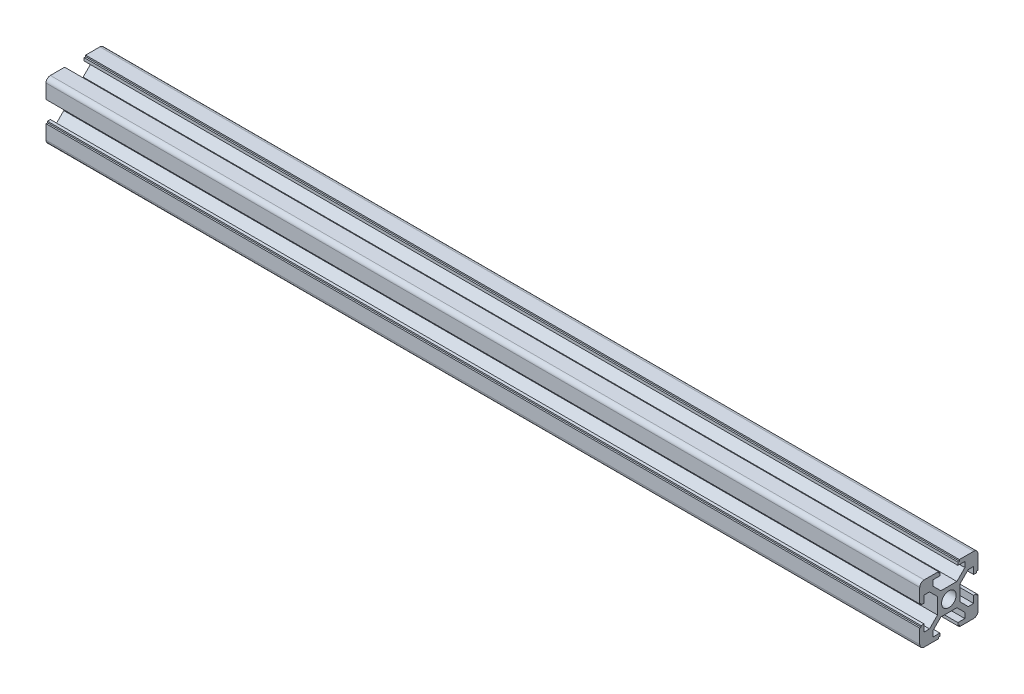
SolidWorks part; units mm, degrees
ref_plane "前视基准面" through (0, 0, 0) normal (0, 0, 1) x (1, 0, 0)
ref_plane "上视基准面" through (0, 0, 0) normal (0, 1, 0) x (1, 0, 0)
ref_plane "右视基准面" through (0, 0, 0) normal (1, 0, 0) x (0, 0, -1)
other "Configuration Table"
sketch "草图1" plane through (0, 0, 0) normal (0, 0, 1) x (1, 0, 0)
  line L0 (0, 0) -> (300, 0)
  dimension "D1" = 300
other "铝型材 20 X 20 X R1.5(1)"
ref_plane "基准面1" through (0, 0, 0) normal (1, 0, 0) x (0, 1, 0)
sketch "Sketch1" plane through (0, 0, 0) normal (1, 0, 0) x (0, 1, 0)
  line L0 (-3.6, 10) -> (-3.6, 9.5)
  line L1 (-3.6, 9.5) -> (-3.1, 9.5)
  line L2 (-3.1, 9.5) -> (-3.1, 8.5)
  line L3 (-3.1, 8.5) -> (-5.5, 8.5)
  line L4 (-8.5, -10) -> (-3.6, -10)
  line L5 (-10, -8.5) -> (-10, -3.6)
  line L6 (8.5, 10) -> (3.6, 10)
  line L7 (10, 8.5) -> (10, 3.6)
  line L8 (0, 14.8756) -> (0, 0) construction
  line L9 (0, 0) -> (14.1675, 0) construction
  line L10 (-5.5, 8.5) -> (-5.5, 6.65)
  line L11 (-5.5, 6.65) -> (-2.75, 3.9)
  line L12 (-2.75, 3.9) -> (2.75, 3.9)
  line L13 (5.5, 6.65) -> (2.75, 3.9)
  line L14 (5.5, 8.5) -> (5.5, 6.65)
  line L15 (3.1, 8.5) -> (5.5, 8.5)
  line L16 (3.1, 9.5) -> (3.1, 8.5)
  line L17 (3.6, 9.5) -> (3.1, 9.5)
  line L18 (3.6, 10) -> (3.6, 9.5)
  line L19 (-3.6, 10) -> (-8.5, 10)
  line L20 (10, 3.6) -> (9.5, 3.6)
  line L21 (9.5, 3.6) -> (9.5, 3.1)
  line L22 (9.5, 3.1) -> (8.5, 3.1)
  line L23 (8.5, 3.1) -> (8.5, 5.5)
  line L24 (8.5, 5.5) -> (6.65, 5.5)
  line L25 (6.65, 5.5) -> (3.9, 2.75)
  line L26 (3.9, 2.75) -> (3.9, -2.75)
  line L27 (6.65, -5.5) -> (3.9, -2.75)
  line L28 (8.5, -5.5) -> (6.65, -5.5)
  line L29 (8.5, -3.1) -> (8.5, -5.5)
  line L30 (9.5, -3.1) -> (8.5, -3.1)
  line L31 (9.5, -3.6) -> (9.5, -3.1)
  line L32 (10, -3.6) -> (9.5, -3.6)
  line L33 (3.6, -10) -> (3.6, -9.5)
  line L34 (3.6, -9.5) -> (3.1, -9.5)
  line L35 (3.1, -9.5) -> (3.1, -8.5)
  line L36 (3.1, -8.5) -> (5.5, -8.5)
  line L37 (5.5, -8.5) -> (5.5, -6.65)
  line L38 (5.5, -6.65) -> (2.75, -3.9)
  line L39 (2.75, -3.9) -> (-2.75, -3.9)
  line L40 (-5.5, -6.65) -> (-2.75, -3.9)
  line L41 (-5.5, -8.5) -> (-5.5, -6.65)
  line L42 (-3.1, -8.5) -> (-5.5, -8.5)
  line L43 (-3.1, -9.5) -> (-3.1, -8.5)
  line L44 (-3.6, -9.5) -> (-3.1, -9.5)
  line L45 (-3.6, -10) -> (-3.6, -9.5)
  line L46 (-10, -3.6) -> (-9.5, -3.6)
  line L47 (-9.5, -3.6) -> (-9.5, -3.1)
  line L48 (-9.5, -3.1) -> (-8.5, -3.1)
  line L49 (-8.5, -3.1) -> (-8.5, -5.5)
  line L50 (-8.5, -5.5) -> (-6.65, -5.5)
  line L51 (-6.65, -5.5) -> (-3.9, -2.75)
  line L52 (-3.9, -2.75) -> (-3.9, 2.75)
  line L53 (-6.65, 5.5) -> (-3.9, 2.75)
  line L54 (-8.5, 5.5) -> (-6.65, 5.5)
  line L55 (-8.5, 3.1) -> (-8.5, 5.5)
  line L56 (-9.5, 3.1) -> (-8.5, 3.1)
  line L57 (-9.5, 3.6) -> (-9.5, 3.1)
  line L58 (-10, 3.6) -> (-9.5, 3.6)
  line L59 (3.6, -10) -> (8.5, -10)
  line L60 (-10, 3.6) -> (-10, 8.5)
  line L61 (10, -3.6) -> (10, -8.5)
  circle A0 centre (0, 0) radius 2.5
  arc A1 (-10, 8.5) -> (-8.5, 10) centre (-8.5, 8.5) cw
  arc A2 (10, 8.5) -> (8.5, 10) centre (8.5, 8.5) ccw
  arc A3 (-8.5, -10) -> (-10, -8.5) centre (-8.5, -8.5) cw
  arc A4 (8.5, -10) -> (10, -8.5) centre (8.5, -8.5) ccw
  point P0 (-10, 0)
  point P1 (10, 0)
  point P2 (0, 10)
  point P3 (0, -10)
  point P4 (0, 0)
  point P5 (-10, -10)
  point P6 (10, -10)
  point P7 (10, 10)
  point P8 (-10, 10)
  point P13 (0, 0)
  point P36 (-10, 10)
  point P39 (10, 10)
  dimension "D1" = 11
  dimension "D2" = 20
  dimension "D3" = 6.2
  dimension "D4" = 7.2
  dimension "D5" = 6.1
  dimension "D6" = 5
  dimension "D7" = 1.5
  dimension "D8" = 45
  dimension "D9" = 0.5
  dimension "D10" = 1
  dimension "D11" = 5.5
